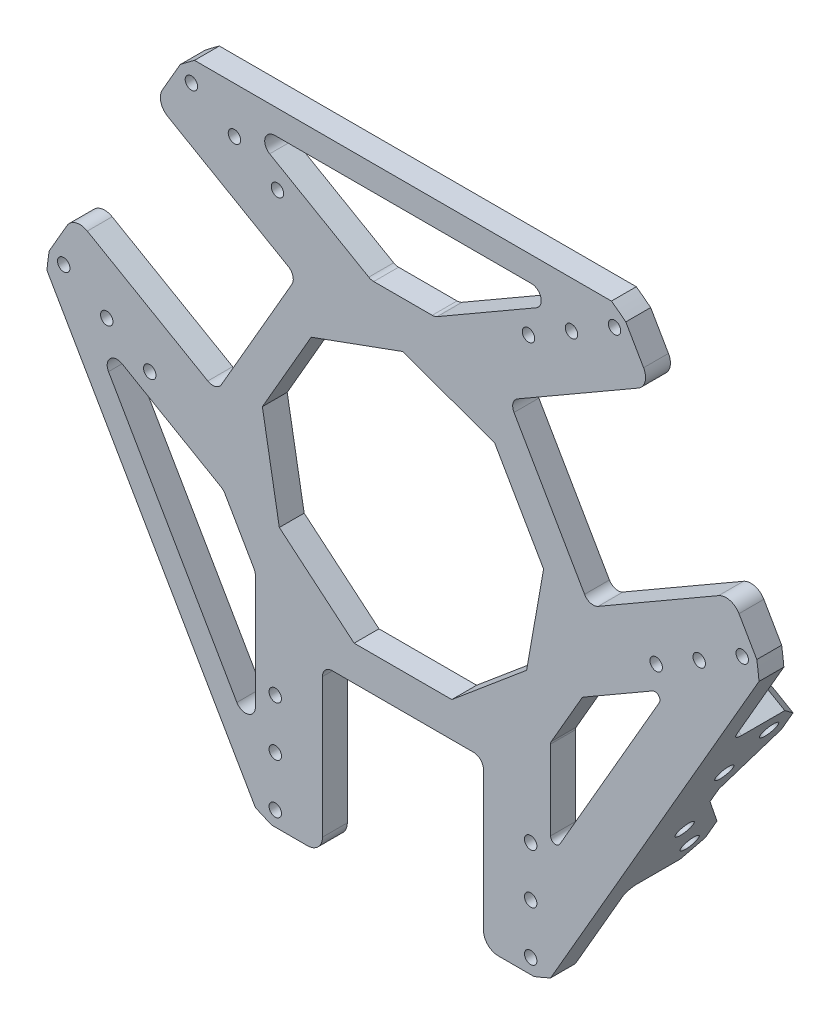
SolidWorks part; units mm, degrees
material "6061 合金"
ref_plane "前视基准面" through (0, 0, 0) normal (0, 0, 1) x (1, 0, 0)
ref_plane "上视基准面" through (0, 0, 0) normal (0, 1, 0) x (1, 0, 0)
ref_plane "右视基准面" through (0, 0, 0) normal (1, 0, 0) x (0, 0, -1)
other "Configuration Table"
sketch "草图1" plane through (0, 0, 0) normal (0, 0, 1) x (1, 0, 0)
  line L0 (0, 0) -> (0, -72) construction
  line L1 (0, 0) -> (-62.3538, 36) construction
  line L2 (0, 0) -> (62.3538, 36) construction
  line L3 (25.7, -64) -> (25.7, -54) construction
  line L4 (-25.7, -64) -> (-25.7, -54) construction
  circle A0 centre (0, 0) radius 72
  circle A1 centre (25.7, -64) radius 1.25
  circle A2 centre (25.7, -54) radius 1.25
  circle A3 centre (25.7, -44) radius 1.25
  circle A4 centre (-25.7, -44) radius 1.25
  circle A5 centre (-25.7, -54) radius 1.25
  circle A6 centre (-25.7, -64) radius 1.25
  circle A7 centre (-25.2551, 44.2569) radius 1.25
  circle A8 centre (-33.9154, 49.2569) radius 1.25
  circle A9 centre (-42.5756, 54.2569) radius 1.25
  circle A10 centre (-50.9551, -0.2569) radius 1.25
  circle A11 centre (-59.6154, 4.7431) radius 1.25
  circle A12 centre (-68.2756, 9.7431) radius 1.25
  circle A13 centre (50.9551, -0.2569) radius 1.25
  circle A14 centre (59.6154, 4.7431) radius 1.25
  circle A15 centre (68.2756, 9.7431) radius 1.25
  circle A16 centre (25.2551, 44.2569) radius 1.25
  circle A17 centre (33.9154, 49.2569) radius 1.25
  circle A18 centre (42.5756, 54.2569) radius 1.25
  point P8 (0, 0)
  point P47 (0, 0)
  dimension "D1" = 144
  dimension "D3" = 2.5
  dimension "D4" = 25.7
  dimension "D7" = 44
  dimension "D6" = 10
  dimension "D5" = 3
  dimension "D2" = 3
  dimension "D8" = 3
extrude "凸台-拉伸1" add sketch "草图1" along normal blind 5
sketch "草图3" plane through (0, 0, 5) normal (0, 0, 1) x (1, 0, 0)
  line L0 (0, 0) -> (0, -72) construction
  line L1 (16.2, -36) -> (16.2, -70.1538)
  line L2 (14.2, -34) -> (-14.2, -34)
  line L3 (-16.2, -36) -> (-16.2, -70.1538)
  line L4 (-23.0769, 32.0296) -> (-52.655, 49.1065)
  line L5 (-36.5449, 4.7024) -> (-22.3449, 29.2976)
  line L6 (-39.2769, 3.9704) -> (-68.855, 21.0473)
  line L7 (39.2769, 3.9704) -> (68.855, 21.0473)
  line L8 (22.3449, 29.2976) -> (36.5449, 4.7024)
  line L9 (23.0769, 32.0296) -> (52.655, 49.1065)
  circle A0 centre (0, 0) radius 72 construction
  circle A2 centre (25.7, -44) radius 1.25 construction
  arc A3 (16.2, -36) -> (14.2, -34) centre (14.2, -36) ccw
  arc A4 (-16.2, -70.1538) -> (16.2, -70.1538) centre (0, 0) ccw
  arc A5 (-16.2, -36) -> (-14.2, -34) centre (-14.2, -36) cw
  arc A6 (-23.0769, 32.0296) -> (-22.3449, 29.2976) centre (-24.0769, 30.2976) cw
  arc A7 (-39.2769, 3.9704) -> (-36.5449, 4.7024) centre (-38.2769, 5.7024) ccw
  arc A8 (39.2769, 3.9704) -> (36.5449, 4.7024) centre (38.2769, 5.7024) cw
  arc A9 (23.0769, 32.0296) -> (22.3449, 29.2976) centre (24.0769, 30.2976) ccw
  arc A10 (-52.655, 49.1065) -> (-68.855, 21.0473) centre (0, 0) ccw
  arc A11 (68.855, 21.0473) -> (52.655, 49.1065) centre (0, 0) ccw
  point P17 (0, -34)
  point P36 (0, 0)
  dimension "D3" = 2
  dimension "D1" = 16.2
  dimension "D2" = 10
  dimension "D4" = 3
extrude "切除-拉伸2" cut sketch "草图3" against normal blind 10
sketch "草图5" plane through (0, 0, 5) normal (0, 0, 1) x (1, 0, 0)
  line L0 (-41.9517, 58.5154) -> (-6.4179, 38)
  line L1 (-6.4179, 38) -> (6.4179, 38)
  line L2 (-23.0769, 32.0296) -> (-52.655, 49.1065) construction
  line L3 (0, 0) -> (0, 72) construction
  line L4 (41.9517, 58.5154) -> (6.4179, 38)
  line L5 (71.6517, 7.0735) -> (36.1179, -13.4419)
  line L6 (29.7, -65.5889) -> (29.7, -24.5581)
  line L7 (36.1179, -13.4419) -> (29.7, -24.5581)
  line L8 (-29.7, -65.5889) -> (-29.7, -24.5581)
  line L9 (-71.6517, 7.0735) -> (-36.1179, -13.4419)
  line L10 (-29.7, -24.5581) -> (-36.1179, -13.4419)
  arc A0 (52.655, 49.1065) -> (-52.655, 49.1065) centre (0, 0) ccw construction
  circle A1 centre (-33.9154, 49.2569) radius 1.25 construction
  arc A2 (41.9517, 58.5154) -> (-41.9517, 58.5154) centre (0, 0) ccw
  arc A3 (29.7, -65.5889) -> (71.6517, 7.0735) centre (0, 0) ccw
  arc A4 (-71.6517, 7.0735) -> (-29.7, -65.5889) centre (0, 0) ccw
  point P14 (0, 38)
  point P25 (0, 0)
  dimension "D1" = 4
  dimension "D2" = 38
  dimension "D3" = 3
extrude "切除-拉伸3" cut sketch "草图5" against normal blind 10
sketch "草图6" plane through (0, 0, 5) normal (0, 0, 1) x (1, 0, 0)
  line L0 (-71.6517, 7.0735) -> (-29.7, -65.5889)
  line L1 (-29.7, -65.5889) -> (-29.7, -55.5889)
  line L2 (-29.7, -65.5889) -> (-29.7, -24.5581) construction
  line L3 (-29.7, -55.5889) -> (-62.9914, 2.0735)
  line L4 (-36.1179, -13.4419) -> (-71.6517, 7.0735) construction
  line L5 (-62.9914, 2.0735) -> (-71.6517, 7.0735)
  line L6 (33.2914, 53.5154) -> (41.9517, 58.5154)
  line L7 (-33.2914, 53.5154) -> (33.2914, 53.5154)
  line L8 (41.9517, 58.5154) -> (-41.9517, 58.5154)
  line L9 (-41.9517, 58.5154) -> (-33.2914, 53.5154)
  line L10 (29.7, -55.5889) -> (29.7, -65.5889)
  line L11 (62.9914, 2.0735) -> (29.7, -55.5889)
  line L12 (29.7, -65.5889) -> (71.6517, 7.0735)
  line L13 (71.6517, 7.0735) -> (62.9914, 2.0735)
  point P20 (0, 0)
  dimension "D1" = 5
  dimension "D2" = 3
extrude "凸台-拉伸2" add sketch "草图6" against normal blind 5
sketch "草图7" plane through (0, 0, 5) normal (0, 0, 1) x (1, 0, 0)
  line L0 (14.2, -34) -> (-14.2, -34) construction
  line L1 (-24.8833, -14.3664) -> (-9.8272, -27)
  line L2 (-9.8272, -27) -> (9.8272, -27)
  line L3 (9.8272, -27) -> (24.8833, -14.3664)
  line L4 (24.8833, -14.3664) -> (28.2963, 4.9894)
  line L5 (28.2963, 4.9894) -> (18.4691, 22.0106)
  line L6 (18.4691, 22.0106) -> (0, 28.7328)
  line L7 (0, 28.7328) -> (-18.4691, 22.0106)
  line L8 (-18.4691, 22.0106) -> (-28.2963, 4.9894)
  line L9 (-28.2963, 4.9894) -> (-24.8833, -14.3664)
  circle A0 centre (0, 0) radius 27 construction
  dimension "D1" = 7
extrude "切除-拉伸4" cut sketch "草图7" against normal blind 6
sketch "草图10" plane through (0, 0, 5) normal (0, 0, 1) x (1, 0, 0)
  line L0 (-68.855, 21.0473) -> (-39.2769, 3.9704) construction
  line L3 (-44.8423, 56.3309) -> (-49.9237, 47.5296)
  line L4 (-68.855, 21.0473) -> (-66.1237, 19.4704)
  line L5 (-23.0769, 32.0296) -> (-52.655, 49.1065) construction
  line L6 (-49.9237, 47.5296) -> (-52.655, 49.1065)
  line L7 (-66.1237, 19.4704) -> (-71.2051, 10.6691)
  line L8 (52.655, 49.1065) -> (49.9237, 47.5296)
  line L9 (49.9237, 47.5296) -> (44.8423, 56.3309)
  line L10 (66.1237, 19.4704) -> (68.855, 21.0473)
  line L11 (71.2051, 10.6691) -> (66.1237, 19.4704)
  line L12 (16.2, -70.1538) -> (16.2, -67)
  line L13 (16.2, -67) -> (26.3629, -67)
  line L14 (-16.2, -67) -> (-16.2, -70.1538)
  line L15 (-26.3629, -67) -> (-16.2, -67)
  circle A0 centre (-68.2756, 9.7431) radius 1.25 construction
  arc A2 (-68.855, 21.0473) -> (-71.6517, 7.0735) centre (0, 0) ccw construction
  arc A3 (-68.855, 21.0473) -> (-71.2051, 10.6691) centre (0, 0) ccw
  arc A4 (-41.9517, 58.5154) -> (-52.655, 49.1065) centre (0, 0) ccw construction
  arc A5 (-44.8423, 56.3309) -> (-52.655, 49.1065) centre (0, 0) ccw
  circle A6 centre (-42.5756, 54.2569) radius 1.25 construction
  arc A7 (52.655, 49.1065) -> (44.8423, 56.3309) centre (0, 0) ccw
  arc A8 (71.2051, 10.6691) -> (68.855, 21.0473) centre (0, 0) ccw
  arc A9 (16.2, -70.1538) -> (26.3629, -67) centre (0, 0) ccw
  arc A10 (-26.3629, -67) -> (-16.2, -70.1538) centre (0, 0) ccw
  point P32 (0, 0)
  dimension "D2" = 3
  dimension "D1" = 3
  dimension "D3" = 3
extrude "切除-拉伸5" cut sketch "草图10" against normal blind 10
fillet "圆角1" radius 3 6 edges at (16.2, -67, 2.5) (-16.2, -67, 2.5) (49.9237, 47.5296, 2.5) (66.1237, 19.4704, 2.5) (-66.1237, 19.4704, 2.5) (-49.9237, 47.5296, 2.5)
sketch "草图12" plane through (0, 0, 0) normal (0, 0, -1) x (-1, 0, 0)
  line L0 (-29.7, -24.5581) -> (-29.7, -55.5889) construction
  line L1 (-36.1179, -13.4419) -> (-29.7, -24.5581) construction
  line L2 (-62.9914, 2.0735) -> (-36.1179, -13.4419) construction
  line L3 (-62.9914, 2.0735) -> (-29.7, -55.5889) construction
  line L4 (-29.7, -24.5581) -> (-29.7, -55.5889)
  line L5 (-36.1179, -13.4419) -> (-29.7, -24.5581)
  line L6 (-62.9914, 2.0735) -> (-36.1179, -13.4419)
  line L7 (-62.9914, 2.0735) -> (-29.7, -55.5889)
extrude "凸台-拉伸3" add sketch "草图12" against normal blind 5
sketch "草图13" plane through (50.6758, -29.2577, 0) normal (0.866, -0.5, 0) x (0, 0, -1)
  line L0 (0, -41.9517) -> (0, 41.9517) construction
  line L1 (0, 21) -> (10.6569, 21)
  line L2 (0, 21) -> (0, -21)
  line L3 (0, -21) -> (10.6569, -21)
  line L4 (14, 17.6569) -> (14, 12.966)
  line L5 (0, 0) -> (-5, 0) construction
  line L6 (-5, -41.9517) -> (-5, 41.9517) construction
  line L7 (14, 12.966) -> (7, 1.766)
  line L8 (7, 1.766) -> (7, -1.766)
  line L9 (7, -1.766) -> (14, -12.966)
  line L10 (14, -12.966) -> (14, -17.6569)
  line L11 (10.6569, -21) -> (14, -17.6569)
  line L12 (10.6569, 21) -> (14, 17.6569)
  circle A0 centre (5, 8) radius 1.75
  circle A1 centre (10, 16) radius 1.75
  circle A2 centre (5, -8) radius 1.75
  circle A3 centre (10, -16) radius 1.75
  point P1 (14, -21)
  dimension "D3" = 5
  dimension "D4" = 8
  dimension "D5" = 3.5
  dimension "D6" = 3.5
  dimension "D7" = 5
  dimension "D8" = 8
  dimension "D2" = 42
  dimension "D9" = 4
  dimension "D10" = 5
  dimension "D11" = 5
  dimension "D12" = 5
  dimension "D13" = 5
  dimension "D14" = 7
  dimension "D15" = 4
  dimension "D16" = 135
extrude "凸台-拉伸4" add sketch "草图13" against normal blind 5
cosmetic thread "装饰螺纹线1" parameters "D2"=4
cosmetic thread "装饰螺纹线2" parameters "D2"=4
cosmetic thread "装饰螺纹线3" parameters "D2"=4
cosmetic thread "装饰螺纹线4" parameters "D2"=4
fillet "圆角2" radius 2 3 edges at (59.0108, -9.8212, 0) (46.3457, -26.7577, 0) (38.0108, -46.1942, 0)
sketch "草图14" plane through (0, 0, 0) normal (0, 0, -1) x (-1, 0, 0)
  line L0 (29.7, -55.5889) -> (29.7, -24.5581) construction
  line L1 (36.1179, -13.4419) -> (62.9914, 2.0735) construction
  line L2 (29.7, -24.5581) -> (36.1179, -13.4419) construction
  line L3 (29.7, -55.5889) -> (29.7, -24.5581) construction
  line L4 (36.1179, -13.4419) -> (62.9914, 2.0735) construction
  line L5 (29.7, -24.5581) -> (36.1179, -13.4419) construction
  line L6 (-29.7, -24.826) -> (-29.7, -40.826)
  line L7 (-35.984, -13.674) -> (-29.834, -24.326)
  line L8 (-50.2064, -5.3079) -> (-36.35, -13.3079)
  line L9 (-51.5724, -6.674) -> (-31.566, -41.326)
  arc A0 (-35.984, -13.674) -> (-36.35, -13.3079) centre (-36.85, -14.174) ccw
  arc A1 (-29.7, -24.826) -> (-29.834, -24.326) centre (-30.7, -24.826) ccw
  arc A2 (-29.7, -40.826) -> (-31.566, -41.326) centre (-30.7, -40.826) cw
  arc A3 (-51.5724, -6.674) -> (-50.2064, -5.3079) centre (-50.7064, -6.174) cw
  point P11 (0, 0)
  dimension "D4" = 1
  dimension "D2" = 120
  dimension "D3" = 10
  dimension "D1" = 2
extrude "切除-拉伸6" cut sketch "草图14" against normal blind 5
fillet "圆角3" radius 2 8 edges at (-29.7, -55.5889, 2.5) (-29.7, -24.5581, 2.5) (-36.1179, -13.4419, 2.5) (-62.9914, 2.0735, 2.5) (-33.2914, 53.5154, 2.5) (-6.4179, 38, 2.5) (6.4179, 38, 2.5) (33.2914, 53.5154, 2.5)
